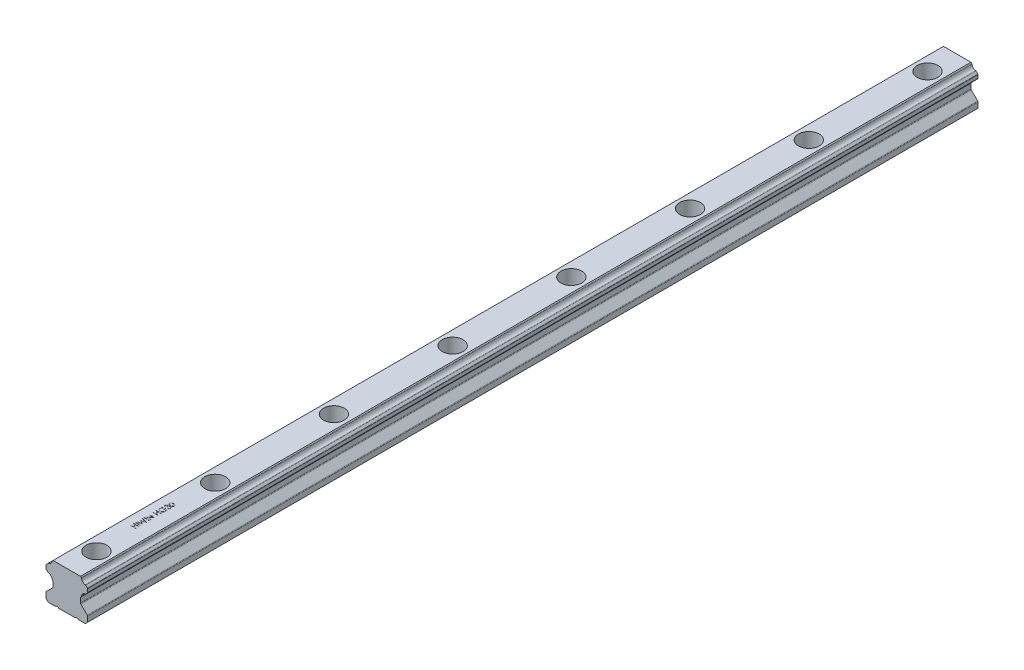
SolidWorks part; units mm, degrees
material "镀铬不锈钢"
ref_plane "前视基准面" through (0, 0, 0) normal (0, 0, 1) x (1, 0, 0)
ref_plane "上视基准面" through (0, 0, 0) normal (0, 1, 0) x (1, 0, 0)
ref_plane "右视基准面" through (0, 0, 0) normal (1, 0, 0) x (0, 0, -1)
sketch "草图1" plane through (0, 0, 0) normal (0, 0, 1) x (1, 0, 0)
  line L28 (13.8243, 21.4316) -> (12.7166, 22.5393)
  line L29 (-6.05, 0.5) -> (-5.55, 0)
  line L30 (9.2558, 26) -> (-9.2558, 26)
  line L31 (-7.25, 0.5) -> (-6.05, 0.5)
  line L32 (7.25, 0.5) -> (7.75, 0)
  line L33 (7.75, 0) -> (12.5, 0)
  line L34 (-12.7166, 22.5393) -> (-13.8243, 21.4316)
  line L35 (9.3, 10.4725) -> (9.3, 13.7069)
  line L36 (14, 18.9868) -> (14, 21.0073)
  line L37 (-5.55, 0) -> (5.55, 0)
  line L38 (-14, 21.0073) -> (-14, 18.9868)
  line L39 (12.723, 17.4613) -> (13.8243, 18.5626)
  line L40 (-9.7478, 14.4861) -> (-9.5343, 14.2726)
  line L41 (13.7657, 5.6754) -> (9.5343, 9.9068)
  line L42 (-9.3, 13.7069) -> (-9.3, 10.4725)
  line L43 (-14, 1.5) -> (-12.5, 0)
  line L44 (12.5, 0) -> (14, 1.5)
  line L45 (9.7486, 25.5072) -> (9.2558, 26)
  line L46 (5.55, 0) -> (6.05, 0.5)
  line L47 (9.5343, 14.2726) -> (9.7478, 14.4861)
  line L48 (-14, 5.1097) -> (-14, 1.5)
  line L49 (14, 1.5) -> (14, 5.1097)
  line L50 (-12.5, 0) -> (-7.75, 0)
  line L51 (-13.8243, 18.5626) -> (-12.723, 17.4613)
  line L52 (6.05, 0.5) -> (7.25, 0.5)
  line L53 (-9.2558, 26) -> (-9.7486, 25.5072)
  line L54 (-7.75, 0) -> (-7.25, 0.5)
  line L55 (-9.5343, 9.9068) -> (-13.7657, 5.6754)
  arc A22 (-12.3683, 22.7102) -> (-12.7166, 22.5393) centre (-12.2923, 22.115) ccw
  arc A23 (-12.3683, 22.7102) -> (-9.9195, 25.159) centre (-12.7267, 25.5174) ccw
  arc A24 (-12.723, 17.4613) -> (-12.3736, 17.2902) centre (-12.2987, 17.8856) ccw
  arc A25 (12.3736, 17.2902) -> (12.723, 17.4613) centre (12.2987, 17.8856) ccw
  arc A26 (-9.7486, 25.5072) -> (-9.9195, 25.159) centre (-9.3243, 25.083) ccw
  arc A27 (12.3736, 17.2902) -> (9.9188, 14.8355) centre (12.7267, 14.4824) ccw
  arc A28 (-13.7657, 5.6754) -> (-14, 5.1097) centre (-13.2, 5.1097) ccw
  arc A29 (13.8243, 18.5626) -> (14, 18.9868) centre (13.4, 18.9868) ccw
  arc A30 (-9.5343, 9.9068) -> (-9.3, 10.4725) centre (-10.1, 10.4725) ccw
  arc A31 (9.7478, 14.4861) -> (9.9188, 14.8355) centre (9.3235, 14.9104) ccw
  arc A32 (-9.3, 13.7069) -> (-9.5343, 14.2726) centre (-10.1, 13.7069) ccw
  arc A33 (9.5343, 14.2726) -> (9.3, 13.7069) centre (10.1, 13.7069) ccw
  arc A34 (-9.9188, 14.8355) -> (-9.7478, 14.4861) centre (-9.3235, 14.9104) ccw
  arc A35 (9.3, 10.4725) -> (9.5343, 9.9068) centre (10.1, 10.4725) ccw
  arc A36 (-9.9188, 14.8355) -> (-12.3736, 17.2902) centre (-12.7267, 14.4824) ccw
  arc A37 (14, 5.1097) -> (13.7657, 5.6754) centre (13.2, 5.1097) ccw
  arc A38 (12.7166, 22.5393) -> (12.3683, 22.7102) centre (12.2923, 22.115) ccw
  arc A39 (9.9195, 25.159) -> (9.7486, 25.5072) centre (9.3243, 25.083) ccw
  arc A40 (-14, 18.9868) -> (-13.8243, 18.5626) centre (-13.4, 18.9868) ccw
  arc A41 (14, 21.0073) -> (13.8243, 21.4316) centre (13.4, 21.0073) ccw
  arc A42 (-13.8243, 21.4316) -> (-14, 21.0073) centre (-13.4, 21.0073) ccw
  arc A43 (9.9195, 25.159) -> (12.3683, 22.7102) centre (12.7267, 25.5174) ccw
extrude "凸台-拉伸1" add sketch "草图1" against normal blind 600
hole_wizard "M8 六角凹头螺钉的柱形沉头孔1" positions "草图3" profile "草图2" counterbore size "M8" standard "ISO" end condition through all
sketch "草图3" plane through (-4.5206, 26, -44.9949) normal (0, 1, 0) x (-1, 0, 0)
  point P0 (-4.5206, 24.9949)
  dimension "D1" = 20
sketch "草图2" plane through (0, 26, -20) normal (1, 0, 0) x (0, 0, 1)
  line L0 (0, 0) -> (0, 26)
  line L1 (0, 26) -> (4.5, 26)
  line L3 (4.5, 26) -> (4.5, 12)
  line L4 (4.5, 12) -> (7, 12)
  line L5 (7, 12) -> (7, 0)
  line L7 (7, 0) -> (0, 0)
  line L11 (0, -6.35) -> (0, 107.95) construction
  dimension "通孔孔直径" = 9
  dimension "通孔孔深度" = 26
  dimension "柱形沉头孔直径" = 14
  dimension "柱形沉头孔深度" = 12
pattern_linear "阵列(线性)1" count 8 spacing 80 along (0, 0, -1) of "M8 六角凹头螺钉的柱形沉头孔1"
sketch "草图6" plane through (0, 26, 0) normal (0, 1, 0) x (1, 0, 0)
  line L0 (0, 20) -> (0, 100) construction
  text T0 "HIWIN HG30"
extrude "切除-拉伸1" cut sketch "草图6" against normal blind 0.1
equation "\"D1@凸台-拉伸1\" = 2 * \"D1@草图3\" + \"D3@阵列(线性)1\" *  ( \"D1@阵列(线性)1\"  - 1) "
